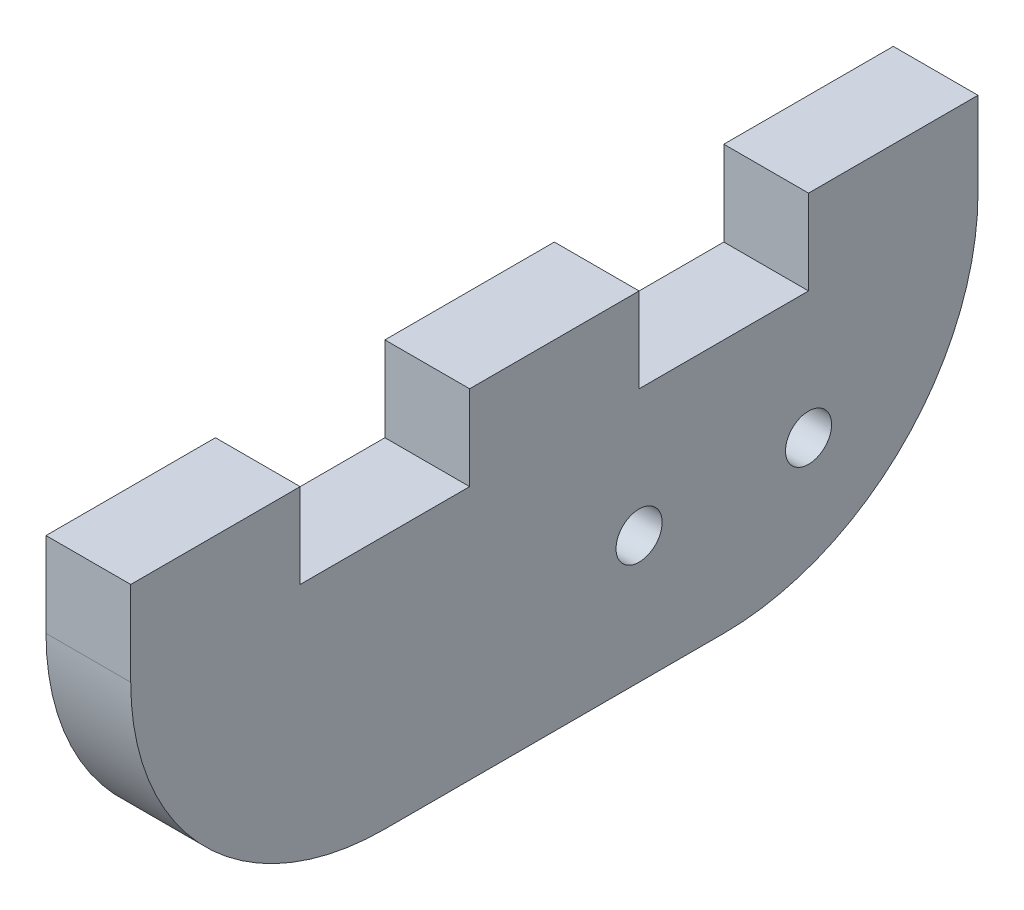
SolidWorks part; units mm, degrees
ref_plane "Front Plane" through (0, 0, 0) normal (0, 0, 1) x (1, 0, 0)
ref_plane "Top Plane" through (0, 0, 0) normal (0, 1, 0) x (1, 0, 0)
ref_plane "Right Plane" through (0, 0, 0) normal (1, 0, 0) x (0, 0, -1)
sketch "Sketch1" plane through (0, 0, 0) normal (1, 0, 0) x (0, 0, -1)
  line L0 (0, 0) -> (0, 6.35)
  line L1 (0, 6.35) -> (-12.7, 6.35)
  line L2 (-12.7, 6.35) -> (-12.7, 0)
  line L3 (-12.7, 0) -> (-25.4, 0)
  line L4 (-25.4, 0) -> (-25.4, 6.35)
  line L5 (-25.4, 6.35) -> (-38.1, 6.35)
  line L6 (-38.1, 6.35) -> (-38.1, 0)
  line L7 (-38.1, 0) -> (-50.8, 0)
  line L8 (-50.8, 0) -> (-50.8, 6.35)
  line L9 (-50.8, 6.35) -> (-63.5, 6.35)
  line L10 (-63.5, 6.35) -> (-63.5, -19.05)
  line L11 (-63.5, -19.05) -> (0, -19.05)
  line L12 (0, -19.05) -> (0, 0)
  dimension "D1" = 6.35
  dimension "D2" = 12.7
  dimension "D3" = 25.4
extrude "Boss-Extrude1" add sketch "Sketch1" along normal mid plane 6.35
hole_wizard "#8-32 Tapped Hole1" positions "Sketch3" profile "Sketch2" tap size "#8-32" standard "ANSI Inch" end condition through all
sketch "Sketch3" plane through (3.175, 0, 0) normal (1, 0, 0) x (0, 0, -1)
  line L0 (-25.4, 0) -> (-25.4, -19.05) construction
  line L1 (-63.5, -19.05) -> (0, -19.05) construction
  line L3 (-25.4, -9.525) -> (-50025.4, -9.525) construction
  line L4 (0, -19.05) -> (0, 6.35) construction
  point P0 (-12.7, -9.525)
  point P2 (-25.4, -9.525)
  point P14 (-25.4, -9.525)
  dimension "D1" = 12.7
sketch "Sketch2" plane through (3.175, -9.525, 12.7) normal (0, 1, 0) x (0, 0, -1)
  line L0 (0, 0) -> (0, 6.35)
  line L1 (0, 6.35) -> (1.7272, 6.35)
  line L2 (1.7272, 6.35) -> (1.7272, 0)
  line L5 (1.7272, 0) -> (0, 0)
  line L11 (0, -6.35) -> (0, 107.95) construction
  dimension "Thru Tap Drill Dia." = 3.4544
  dimension "Thru Tap Drill Depth" = 6.35
cosmetic thread "Hole Thread1" parameters "D2"=4.1656
cosmetic thread "Hole Thread2" parameters "D2"=4.1656
fillet "Fillet1" radius 19.05 2 edges at (0, -19.05, 0) (0, -19.05, 63.5)
